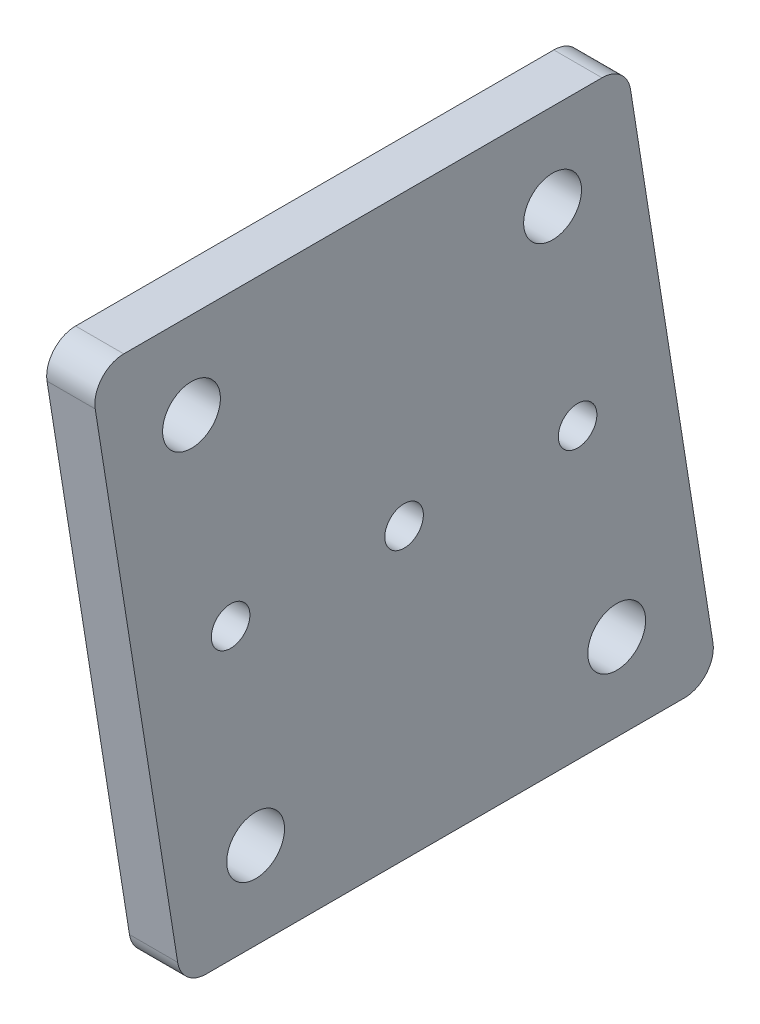
SolidWorks part; units mm, degrees
ref_plane "Front Plane" through (0, 0, 0) normal (0, 0, 1) x (1, 0, 0)
ref_plane "Top Plane" through (0, 0, 0) normal (0, 1, 0) x (1, 0, 0)
ref_plane "Right Plane" through (0, 0, 0) normal (1, 0, 0) x (0, 0, -1)
sketch "Sketch1" plane through (0, 0, 0) normal (1, 0, 0) x (0, 0, -1)
  line L0 (-1.1006, 45.3033) -> (9.4713, -21.4449) construction
  line L1 (-1.1006, 45.3033) -> (24.2111, 45.3033) construction
  line L2 (24.2111, 45.3033) -> (34.783, -21.4449) construction
  line L3 (34.783, -21.4449) -> (9.4713, -21.4449) construction
  line L4 (0, 0) -> (37.4612, 0) construction
  line L5 (0, 0) -> (-6.6521, 42) construction
  line L6 (37.4612, 0) -> (30.8091, 42) construction
  line L7 (-6.6521, 42) -> (30.8091, 42) construction
  line L8 (-3.3261, 21) -> (34.1351, 21) construction
  line L9 (-4.118, 26) -> (33.3432, 26) construction
  line L10 (-2.5342, 16) -> (34.9271, 16) construction
  line L11 (-7.6867, -9) -> (47.9989, -9)
  line L12 (47.9989, -9) -> (38.4958, 51)
  line L13 (38.4958, 51) -> (-17.1898, 51)
  line L14 (-17.1898, 51) -> (-7.6867, -9)
  circle A0 centre (0, 0) radius 6 construction
  circle A1 centre (0, 0) radius 9 construction
  circle A2 centre (0, 0) radius 3
  circle A3 centre (37.4612, 0) radius 3
  circle A4 centre (37.4612, 0) radius 6 construction
  circle A5 centre (37.4612, 0) radius 9 construction
  circle A6 centre (-6.6521, 42) radius 3
  circle A7 centre (-6.6521, 42) radius 6 construction
  circle A8 centre (-6.6521, 42) radius 9 construction
  circle A9 centre (30.8091, 42) radius 3
  circle A10 centre (30.8091, 42) radius 6 construction
  circle A11 centre (30.8091, 42) radius 9 construction
  circle A12 centre (15.4045, 21) radius 2
  circle A13 centre (-2.5955, 21) radius 2
  circle A14 centre (33.4045, 21) radius 2
  dimension "D1" = 18
  dimension "D2" = 12
  dimension "D3" = 6
  dimension "D9" = 18
  dimension "D10" = 18
  dimension "D11" = 4
  dimension "D4" = 99
  dimension "D5" = 25
  dimension "D6" = 42
  dimension "D7" = 5
  dimension "D8" = 5
  dimension "D12" = 60
extrude "Boss-Extrude1" add sketch "Sketch1" along normal blind 5
fillet "Fillet1" radius 3 4 edges at (2.5, 51, -38.4958) (2.5, -9, -47.9989) (2.5, -9, 7.6867) (2.5, 51, 17.1898)
